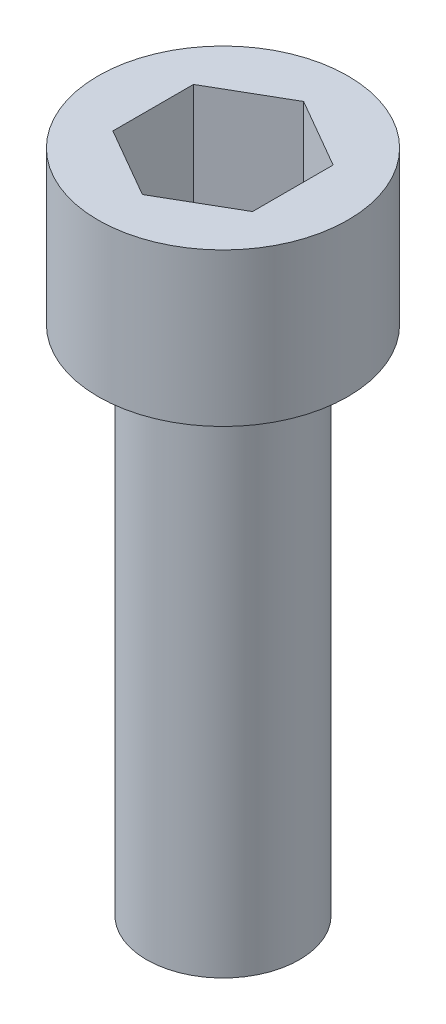
SolidWorks part; units mm, degrees
material "1060 Alloy"
ref_plane "Front Plane" through (0, 0, 0) normal (0, 0, 1) x (1, 0, 0)
ref_plane "Top Plane" through (0, 0, 0) normal (0, 1, 0) x (1, 0, 0)
ref_plane "Right Plane" through (0, 0, 0) normal (1, 0, 0) x (0, 0, -1)
sketch "Sketch1" plane through (0, 0, 0) normal (0, 1, 0) x (1, 0, 0)
  circle A0 centre (0, 0) radius 2.3241
  dimension "D1" = 4.6482
extrude "Boss-Extrude1" add sketch "Sketch1" along normal blind 2.8448
sketch "Sketch3" plane through (0, 2.8448, 0) normal (0, 1, 0) x (1, 0, 0)
  line L0 (0, 0) -> (0, 1.5) construction
  line L1 (-1.299, 0.75) -> (-1.299, -0.75)
  line L8 (-1.299, -0.75) -> (0, -1.5)
  line L9 (0, -1.5) -> (1.299, -0.75)
  line L10 (1.299, -0.75) -> (1.299, 0.75)
  line L11 (1.299, 0.75) -> (0, 1.5)
  line L12 (0, 1.5) -> (-1.299, 0.75)
  circle A0 centre (0, 0) radius 1.299 construction
  point P1 (0, 1.5)
  point P3 (0, 0)
  point P11 (0, 0)
  dimension "D1" = 1.5
extrude "Cut-Extrude1" cut sketch "Sketch3" against normal blind 2
sketch "Sketch4" plane through (0, 0, 0) normal (0, -1, 0) x (1, 0, 0)
  circle A0 centre (0, 0) radius 1.4224
  dimension "D1" = 2.8448
extrude "Boss-Extrude2" add sketch "Sketch4" along normal blind 9.525
